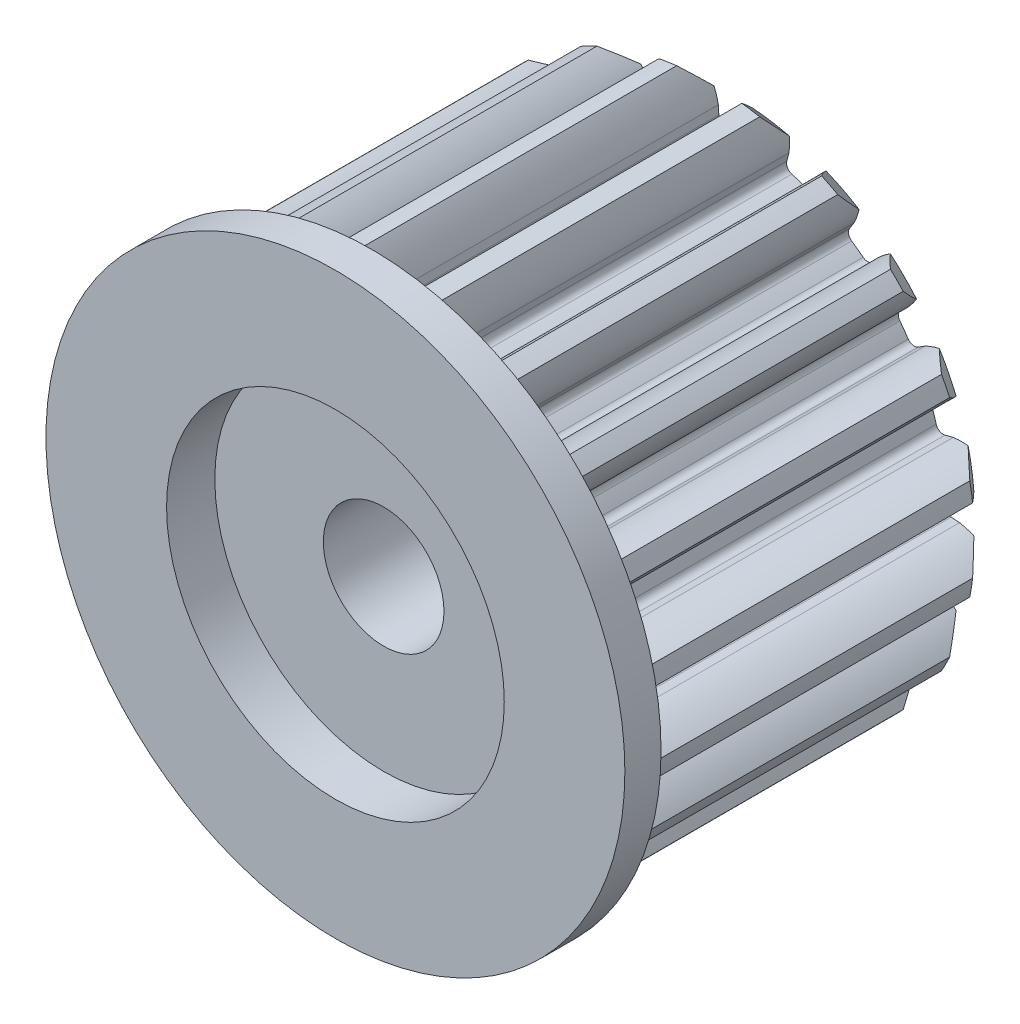
SolidWorks part; units mm, degrees
ref_plane "中间平面" through (0, 0, 0) normal (0, 0, 1) x (1, 0, 0)
ref_plane "上视基准面" through (0, 0, 0) normal (0, 1, 0) x (1, 0, 0)
ref_plane "右视基准面" through (0, 0, 0) normal (1, 0, 0) x (0, 0, -1)
sketch "直齿轮" plane through (0, 0, 0) normal (0, 0, 1) x (1, 0, 0)
  line L0 (0, 0) -> (-0.7846, 9.9692) construction
  line L2 (-0.6279, 9.3759) -> (0, 0)
  line L3 (0, 0) -> (0, 52) construction
  line L4 (0.7846, 9.9692) -> (0, 0) construction
  line L6 (0, 0) -> (0.6279, 9.3759)
  circle A0 centre (0, 0) radius 9.3969
  circle A1 centre (0, 0) radius 8.75
  arc A2 (0.7846, 9.9692) -> (-0.7846, 9.9692) centre (0, 0) ccw
  circle A3 centre (0, 0) radius 11
  spline S0 degree 4 poles (-0.377, 9.3172) (-0.3789, 9.3529) (-0.3861, 9.424) (-0.4237, 9.6212) (-0.5398, 9.9863) (-0.7919, 10.5175) (-1.2445, 11.187) (-1.9436, 11.955) (-2.8883, 12.7226) (-4.0364, 13.4081) (-5.3634, 13.9687) (-6.7487, 14.3609) (-8.169, 14.594) (-9.6766, 14.6815) (-11.5447, 14.5947) (-13.7441, 14.2062) (-16.2074, 13.3864) (-18.7699, 12.0638) (-21.1146, 10.3874) (-23.2107, 8.4106) (-24.8087, 6.4616) (-26.0009, 4.6632) (-26.8734, 3.0927) (-27.4981, 1.7982) (-28.049, 0.4708) (-28.5259, -0.8851) (-29.0296, -2.6093) (-29.4103, -4.3664) (-29.6434, -5.9667) (-29.7665, -7.399) (-29.8074, -8.1726) (-29.8233, -8.6502) (-29.8316, -9.0515) (-29.835, -9.4761) (-29.8332, -9.8266) (-29.8201, -10.4939) (-29.7958, -10.9982) (-29.7598, -11.6224) (-29.713, -12.1716) (-29.6549, -12.7674) (-29.5861, -13.3286) (-29.5263, -13.7702) (-29.4828, -14.0502) (-29.4602, -14.196) knots 0 0 0 0 0 0.002802 0.005604 0.015718 0.02996 0.048734 0.068727 0.096889 0.125051 0.153212 0.181374 0.209535 0.237696 0.271429 0.327752 0.384075 0.440398 0.496721 0.553044 0.609367 0.637529 0.66569 0.693852 0.722013 0.750174 0.778336 0.834659 0.86282 0.876901 0.890982 0.895509 0.900036 0.909091 0.920455 0.931818 0.943182 0.954545 0.965909 0.977273 0.988636 1 1 1 1 1 construction
  spline S1 degree 4 poles (-0.6279, 9.3759) (-0.6297, 9.3882) (-0.6371, 9.4354) (-0.673, 9.608) (-0.7823, 9.9484) (-1.0345, 10.4755) (-1.4862, 11.1394) (-2.1832, 11.9006) (-3.1242, 12.6606) (-4.2671, 13.3383) (-5.5875, 13.8915) (-6.9653, 14.2771) (-8.3774, 14.5046) (-9.8758, 14.5871) (-11.7319, 14.4953) (-13.9164, 14.1027) (-16.3618, 13.2807) (-18.9044, 11.9588) (-21.2293, 10.286) (-23.3065, 8.3154) (-24.8887, 6.3738) (-26.0681, 4.5832) (-26.9305, 3.0199) (-27.5474, 1.7317) (-28.0909, 0.411) (-28.5608, -0.9378) (-29.0562, -2.6527) (-29.4294, -4.4) (-29.6562, -5.9908) (-29.7743, -7.4146) (-29.8126, -8.1834) (-29.827, -8.6581) (-29.8341, -9.0569) (-29.8359, -9.4153) (-29.8349, -9.6292) (-29.832, -9.8217) (-29.8304, -9.9096) knots 0.001826 0.001826 0.001826 0.001826 0.001826 0.002802 0.005604 0.015718 0.02996 0.048734 0.068727 0.096889 0.125051 0.153212 0.181374 0.209535 0.237696 0.271429 0.327752 0.384075 0.440398 0.496721 0.553044 0.609367 0.637529 0.66569 0.693852 0.722013 0.750174 0.778336 0.834659 0.86282 0.876901 0.890982 0.895509 0.900036 0.909091 0.916015 0.916015 0.916015 0.916015 0.916015
  spline S2 degree 4 poles (0.377, 9.3172) (0.3789, 9.3529) (0.3861, 9.424) (0.4237, 9.6212) (0.5398, 9.9863) (0.7919, 10.5175) (1.2445, 11.187) (1.9436, 11.955) (2.8883, 12.7226) (4.0364, 13.4081) (5.3634, 13.9687) (6.7487, 14.3609) (8.169, 14.594) (9.6766, 14.6815) (11.5447, 14.5947) (13.7441, 14.2062) (16.2074, 13.3864) (18.7699, 12.0638) (21.1146, 10.3874) (23.2107, 8.4106) (24.8087, 6.4616) (26.0009, 4.6632) (26.8734, 3.0927) (27.4981, 1.7982) (28.049, 0.4708) (28.5259, -0.8851) (29.0296, -2.6093) (29.4103, -4.3664) (29.6434, -5.9667) (29.7665, -7.399) (29.8074, -8.1726) (29.8233, -8.6502) (29.8316, -9.0515) (29.835, -9.4761) (29.8332, -9.8266) (29.8201, -10.4939) (29.7958, -10.9982) (29.7598, -11.6224) (29.713, -12.1716) (29.6549, -12.7674) (29.5861, -13.3286) (29.5263, -13.7702) (29.4828, -14.0502) (29.4602, -14.196) knots 0 0 0 0 0 0.002802 0.005604 0.015718 0.02996 0.048734 0.068727 0.096889 0.125051 0.153212 0.181374 0.209535 0.237696 0.271429 0.327752 0.384075 0.440398 0.496721 0.553044 0.609367 0.637529 0.66569 0.693852 0.722013 0.750174 0.778336 0.834659 0.86282 0.876901 0.890982 0.895509 0.900036 0.909091 0.920455 0.931818 0.943182 0.954545 0.965909 0.977273 0.988636 1 1 1 1 1 construction
  spline S3 degree 4 poles (0.6279, 9.3759) (0.6297, 9.3882) (0.6371, 9.4354) (0.673, 9.608) (0.7823, 9.9484) (1.0345, 10.4755) (1.4862, 11.1394) (2.1832, 11.9006) (3.1242, 12.6606) (4.2671, 13.3383) (5.5875, 13.8915) (6.9653, 14.2771) (8.3774, 14.5046) (9.8758, 14.5871) (11.7319, 14.4953) (13.9164, 14.1027) (16.3618, 13.2807) (18.9044, 11.9588) (21.2293, 10.286) (23.3065, 8.3154) (24.8887, 6.3738) (26.0681, 4.5832) (26.9305, 3.0199) (27.5474, 1.7317) (28.0909, 0.411) (28.5608, -0.9378) (29.0562, -2.6527) (29.4294, -4.4) (29.6562, -5.9908) (29.7743, -7.4146) (29.8126, -8.1834) (29.827, -8.6581) (29.8341, -9.0569) (29.8359, -9.4153) (29.8349, -9.6292) (29.832, -9.8217) (29.8304, -9.9096) knots 0.001826 0.001826 0.001826 0.001826 0.001826 0.002802 0.005604 0.015718 0.02996 0.048734 0.068727 0.096889 0.125051 0.153212 0.181374 0.209535 0.237696 0.271429 0.327752 0.384075 0.440398 0.496721 0.553044 0.609367 0.637529 0.66569 0.693852 0.722013 0.750174 0.778336 0.834659 0.86282 0.876901 0.890982 0.895509 0.900036 0.909091 0.916015 0.916015 0.916015 0.916015 0.916015
  dimension "基圆直径" = 18.7939
  dimension "齿根圆" = 17.5
  dimension "分度圆" = 20
  dimension "齿顶圆" = 22
  dimension "D1" = 1.5708
sketch "圆" plane through (0, 0, 0) normal (0, 0, 1) x (1, 0, 0)
  circle A0 centre (0, 0) radius 11 construction
  circle A1 centre (0, 0) radius 11
extrude "毛胚" add sketch "圆" along normal mid plane 16.5
chamfer "轮齿倒角" distance 1 angle 45 2 edges at (11, 0, -8.25) (11, 0, 8.25)
sketch "齿形" plane through (0, 0, 0) normal (0, 0, 1) x (1, 0, 0)
  line L4 (0, 0) -> (0.6279, 9.3759) construction
  line L5 (-0.6279, 9.3759) -> (0, 0) construction
  line L6 (0, 0) -> (0.6279, 9.3759)
  line L7 (-0.6279, 9.3759) -> (0, 0)
  circle A4 centre (0, 0) radius 8.75 construction
  circle A5 centre (0, 0) radius 11 construction
  circle A6 centre (0, 0) radius 8.75
  circle A7 centre (0, 0) radius 11
  spline S1 degree 4 poles (-999.13, 9.3961) (42.5519, 3.3624) (1.4353, 5.997) (0.1914, 8.1084) (0.7823, 9.9484) (1.0345, 10.4755) (1.4862, 11.1394) (2.1832, 11.9006) (3.1242, 12.6606) (4.2671, 13.3383) (5.5875, 13.8915) (6.9653, 14.2771) (8.3774, 14.5046) (9.8758, 14.5871) (11.7319, 14.4953) (13.9164, 14.1027) (16.3618, 13.2807) (18.9044, 11.9588) (21.2293, 10.286) (23.3065, 8.3154) (24.8887, 6.3738) (26.0681, 4.5832) (26.9305, 3.0199) (27.5474, 1.7317) (28.0909, 0.411) (28.5608, -0.9378) (29.0562, -2.6527) (29.4294, -4.4) (29.6562, -5.9908) (29.7743, -7.4146) (29.8126, -8.1834) (29.827, -8.6581) (29.8341, -9.0569) (29.8461, -11.3868) (29.705, -8.9109) (29.0082, -67.9919) (35.3566, 990.0008) knots -0.122129 -0.122129 -0.122129 -0.122129 -0.122129 0.002802 0.005604 0.015718 0.02996 0.048734 0.068727 0.096889 0.125051 0.153212 0.181374 0.209535 0.237696 0.271429 0.327752 0.384075 0.440398 0.496721 0.553044 0.609367 0.637529 0.66569 0.693852 0.722013 0.750174 0.778336 0.834659 0.86282 0.876901 0.890982 0.895509 0.900036 0.909091 1.053707 1.053707 1.053707 1.053707 1.053707 only from (0.6279, 9.3759) to (29.8304, -9.9096) construction
  spline S3 degree 4 poles (999.13, 9.3961) (-42.5519, 3.3624) (-1.4353, 5.997) (-0.1914, 8.1084) (-0.7823, 9.9484) (-1.0345, 10.4755) (-1.4862, 11.1394) (-2.1832, 11.9006) (-3.1242, 12.6606) (-4.2671, 13.3383) (-5.5875, 13.8915) (-6.9653, 14.2771) (-8.3774, 14.5046) (-9.8758, 14.5871) (-11.7319, 14.4953) (-13.9164, 14.1027) (-16.3618, 13.2807) (-18.9044, 11.9588) (-21.2293, 10.286) (-23.3065, 8.3154) (-24.8887, 6.3738) (-26.0681, 4.5832) (-26.9305, 3.0199) (-27.5474, 1.7317) (-28.0909, 0.411) (-28.5608, -0.9378) (-29.0562, -2.6527) (-29.4294, -4.4) (-29.6562, -5.9908) (-29.7743, -7.4146) (-29.8126, -8.1834) (-29.827, -8.6581) (-29.8341, -9.0569) (-29.8461, -11.3868) (-29.705, -8.9109) (-29.0082, -67.9919) (-35.3566, 990.0008) knots -0.122129 -0.122129 -0.122129 -0.122129 -0.122129 0.002802 0.005604 0.015718 0.02996 0.048734 0.068727 0.096889 0.125051 0.153212 0.181374 0.209535 0.237696 0.271429 0.327752 0.384075 0.440398 0.496721 0.553044 0.609367 0.637529 0.66569 0.693852 0.722013 0.750174 0.778336 0.834659 0.86282 0.876901 0.890982 0.895509 0.900036 0.909091 1.053707 1.053707 1.053707 1.053707 1.053707 only from (-0.6279, 9.3759) to (-29.8304, -9.9096) construction
  spline S4 degree 4 poles (0.6279, 9.3759) (0.6297, 9.3882) (0.6371, 9.4354) (0.673, 9.608) (0.7823, 9.9484) (1.0345, 10.4755) (1.4862, 11.1394) (2.1832, 11.9006) (3.1242, 12.6606) (4.2671, 13.3383) (5.5875, 13.8915) (6.9653, 14.2771) (8.3774, 14.5046) (9.8758, 14.5871) (11.7319, 14.4953) (13.9164, 14.1027) (16.3618, 13.2807) (18.9044, 11.9588) (21.2293, 10.286) (23.3065, 8.3154) (24.8887, 6.3738) (26.0681, 4.5832) (26.9305, 3.0199) (27.5474, 1.7317) (28.0909, 0.411) (28.5608, -0.9378) (29.0562, -2.6527) (29.4294, -4.4) (29.6562, -5.9908) (29.7743, -7.4146) (29.8126, -8.1834) (29.827, -8.6581) (29.8341, -9.0569) (29.8359, -9.4153) (29.8349, -9.6292) (29.832, -9.8217) (29.8304, -9.9096) knots 0.001826 0.001826 0.001826 0.001826 0.001826 0.002802 0.005604 0.015718 0.02996 0.048734 0.068727 0.096889 0.125051 0.153212 0.181374 0.209535 0.237696 0.271429 0.327752 0.384075 0.440398 0.496721 0.553044 0.609367 0.637529 0.66569 0.693852 0.722013 0.750174 0.778336 0.834659 0.86282 0.876901 0.890982 0.895509 0.900036 0.909091 0.916015 0.916015 0.916015 0.916015 0.916015
  spline S5 degree 4 poles (-0.6279, 9.3759) (-0.6297, 9.3882) (-0.6371, 9.4354) (-0.673, 9.608) (-0.7823, 9.9484) (-1.0345, 10.4755) (-1.4862, 11.1394) (-2.1832, 11.9006) (-3.1242, 12.6606) (-4.2671, 13.3383) (-5.5875, 13.8915) (-6.9653, 14.2771) (-8.3774, 14.5046) (-9.8758, 14.5871) (-11.7319, 14.4953) (-13.9164, 14.1027) (-16.3618, 13.2807) (-18.9044, 11.9588) (-21.2293, 10.286) (-23.3065, 8.3154) (-24.8887, 6.3738) (-26.0681, 4.5832) (-26.9305, 3.0199) (-27.5474, 1.7317) (-28.0909, 0.411) (-28.5608, -0.9378) (-29.0562, -2.6527) (-29.4294, -4.4) (-29.6562, -5.9908) (-29.7743, -7.4146) (-29.8126, -8.1834) (-29.827, -8.6581) (-29.8341, -9.0569) (-29.8359, -9.4153) (-29.8349, -9.6292) (-29.832, -9.8217) (-29.8304, -9.9096) knots 0.001826 0.001826 0.001826 0.001826 0.001826 0.002802 0.005604 0.015718 0.02996 0.048734 0.068727 0.096889 0.125051 0.153212 0.181374 0.209535 0.237696 0.271429 0.327752 0.384075 0.440398 0.496721 0.553044 0.609367 0.637529 0.66569 0.693852 0.722013 0.750174 0.778336 0.834659 0.86282 0.876901 0.890982 0.895509 0.900036 0.909091 0.916015 0.916015 0.916015 0.916015 0.916015
extrude "插齿" cut sketch "齿形" against normal mid plane 16.5 contours S5 A6 S4 A7
fillet "圆角1" [suppressed] radius 0.3
pattern_circular "圆周阵列1" [suppressed] count 20 over 360
fillet "圆角2" radius 0.3 2 edges at (0.5847, 8.7304, 0) (-0.5847, 8.7304, 0)
pattern_circular "圆周阵列2" count 20 over 360 about axis through (0, 0, 8.25) along (0, 0, -1) of "圆角2", "插齿"
sketch "分度圆" plane through (0, 0, 0) normal (0, 0, 1) x (1, 0, 0)
  circle A0 centre (0, 0) radius 10 construction
  circle A1 centre (0, 0) radius 10 construction
sketch "草图1" plane through (0, 0, 8.25) normal (0, 0, 1) x (1, 0, 0)
  circle A0 centre (0, 0) radius 12
  dimension "D1" = 24
extrude "凸台-拉伸1" add sketch "草图1" against normal blind 1.5
sketch "草图2" plane through (0, 0, 8.25) normal (0, 0, 1) x (1, 0, 0)
  circle A0 centre (0, 0) radius 7
  dimension "D1" = 14
extrude "切除-拉伸1" cut sketch "草图2" against normal blind 2
sketch "草图3" plane through (0, 0, 6.25) normal (0, 0, 1) x (1, 0, 0)
  circle A0 centre (0, 0) radius 2.5
  dimension "D1" = 5
extrude "切除-拉伸2" cut sketch "草图3" against normal through all
equation "\"m\" = 1'模数"
equation "\"z\" = 20'齿数"
equation "\"a\"= 20'压力角（常见为20°）"
equation "\"B\" = 16.5'齿宽"
equation "\"C1\"= 1'轮齿倒角（若设为0，则无倒角）"
equation "\"x\"= 0'变位系数（不懂勿动）"
equation "\"ha\"= 1'齿顶高系数（不懂勿动）"
equation "\"c\"= 0.25'顶隙系数（不懂勿动）"
equation "\"基圆直径@直齿轮\"= \"m\" * \"z\" * cos ( \"a\" )"
equation "\"齿根圆@直齿轮\" = \"m\" * ( \"z\" - 2 * ( \"ha\" - \"x\" + \"c\" ) )"
equation "\"分度圆@直齿轮\"=\"m\" * \"z\""
equation "\"齿顶圆@直齿轮\" = \"m\" * ( \"z\" + 2 * ( \"ha\" + \"x\" ) )"
equation "\"R\"= 0.3'齿根圆角"
equation "\"D1\"= \"R\""
equation "\"D1@毛胚\" = \"B\""
equation "\"D1@轮齿倒角\" = IIF ( \"C1\" > 0 , \"C1\" , 0.001 )"
equation "\"轮齿倒角\"= IIF ( \"C1\" > 0 , \"unsuppressed\" , \"suppressed\" )"
equation "\"D1@插齿\" = \"B\""
equation "\"D1@圆周阵列1\" = \"z\""
equation "\"D1@直齿轮\"= \"m\" * ( pi / 2 ) - 2 * \"m\" * tan ( \"a\" ) * \"x\"'作者：机械菌-"
equation "\"D1@圆角1\"=\"R\""
equation "\"圆角1\" = IIF ( \"m\" * ( \"z\" - 2 * ( \"ha\" - \"x\" + \"c\" ) ) > \"m\" * \"z\" * cos ( \"a\" ) , \"unsuppressed\" , \"suppressed\" )"
equation "\"圆周阵列1\"= IIF ( \"m\" * ( \"z\" - 2 * ( \"ha\" - \"x\" + \"c\" ) ) > \"m\" * \"z\" * cos ( \"a\" ) , \"unsuppressed\" , \"suppressed\" )"
equation "\"D1@圆角2\"=\"R\""
equation "\"D1@圆周阵列2\" = \"z\""
equation "\"圆角2\" = IIF ( \"m\" * ( \"z\" - 2 * ( \"ha\" - \"x\" + \"c\" ) ) < \"m\" * \"z\" * cos ( \"a\" ) , \"unsuppressed\" , \"suppressed\" )"
equation "\"圆周阵列2\"= IIF ( \"m\" *  ( \"z\" - 2 *  ( \"ha\" - \"x\" + \"c\" )  )  < \"m\" * \"z\" * cos ( \"a\" )  ,  unsuppressed  ,  suppressed  ) "
